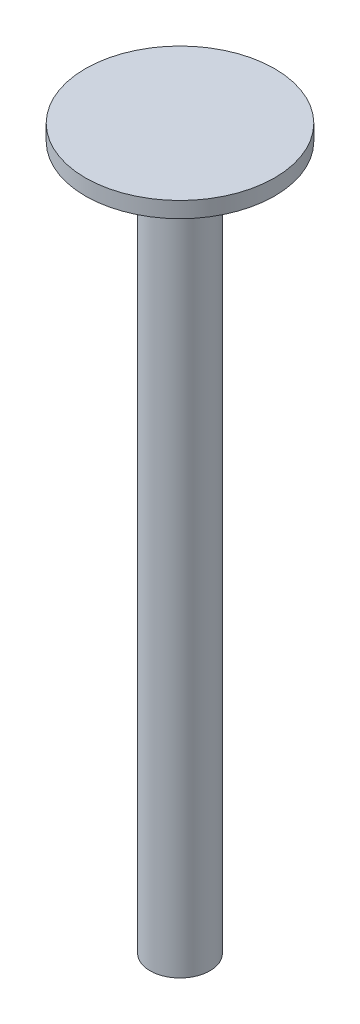
SolidWorks part; units mm, degrees
ref_plane "Front Plane" through (0, 0, 0) normal (0, 0, 1) x (1, 0, 0)
ref_plane "Top Plane" through (0, 0, 0) normal (0, 1, 0) x (1, 0, 0)
ref_plane "Right Plane" through (0, 0, 0) normal (1, 0, 0) x (0, 0, -1)
sketch "Эскиз1" plane through (0, 0, 0) normal (0, 1, 0) x (1, 0, 0)
  circle A0 centre (0, 0) radius 0.95
extrude "Бобышка-Вытянуть1" add sketch "Эскиз1" along normal blind 22.3
sketch "Эскиз3" plane through (0, 22.3, 0) normal (0, 1, 0) x (1, 0, 0)
  circle A0 centre (0, 0) radius 3
extrude "Бобышка-Вытянуть2" add sketch "Эскиз3" along normal blind 0.5
